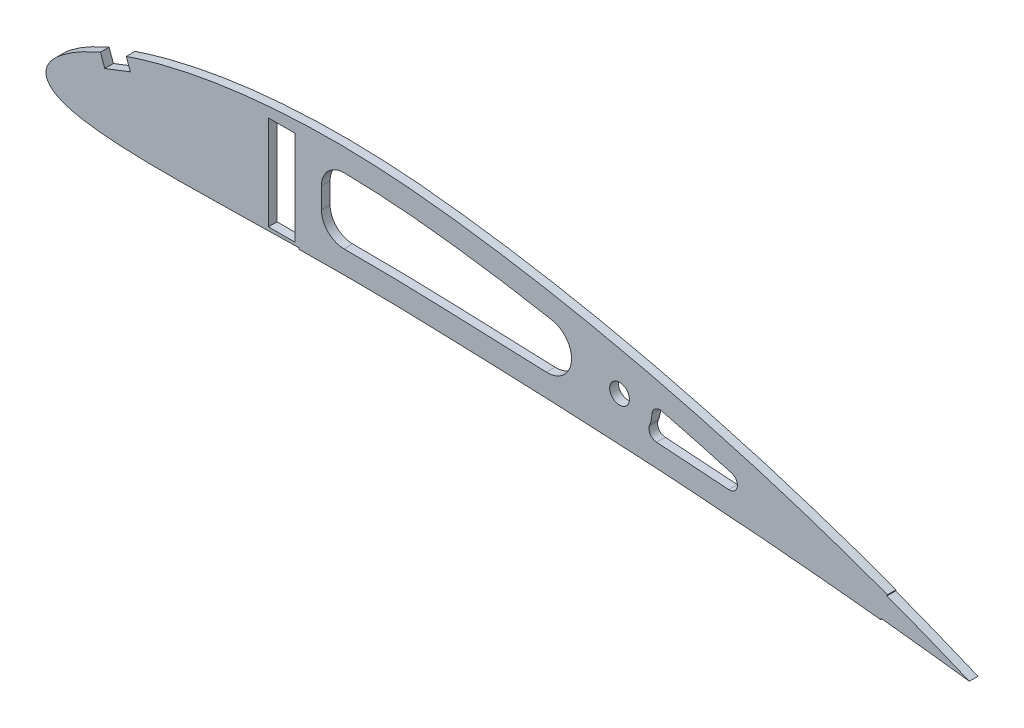
SolidWorks part; units mm, degrees
ref_plane "Front Plane" through (0, 0, 0) normal (0, 0, 1) x (1, 0, 0)
ref_plane "Top Plane" through (0, 0, 0) normal (0, 1, 0) x (1, 0, 0)
ref_plane "Right Plane" through (0, 0, 0) normal (1, 0, 0) x (0, 0, -1)
sketch "Sketch1" plane through (0, 0, 0) normal (0, 0, 1) x (1, 0, 0)
  line L0 (2547.2763, 3279.2563) -> (2536.8623, 3279.2563)
  line L1 (2547.2763, 3242.1233) -> (2536.8623, 3242.1233)
  line L2 (2536.8623, 3279.2563) -> (2536.8623, 3242.1233)
  line L3 (2547.2763, 3279.2563) -> (2547.2763, 3242.1233)
  line L4 (2548.8638, 3240.993) -> (2548.8703, 3240.4726)
  line L5 (2472.4468, 3263.9008) -> (2470.7661, 3268.615)
  line L6 (2482.5221, 3267.7862) -> (2480.9228, 3272.272)
  line L7 (2780.3662, 3238.0365) -> (2780.5427, 3238.5099)
  line L8 (2778.0193, 3229.2488) -> (2777.9678, 3228.7249)
  line L9 (2557.7538, 3266.5426) -> (2557.7538, 3258.3782)
  line L10 (2472.4468, 3263.9008) -> (2482.5221, 3267.7862)
  circle A0 centre (2675.1058, 3254.3467) radius 3.8862
  arc A1 (2686.9168, 3249.475) -> (2687.8696, 3253.7841) centre (2675.1058, 3254.3467) ccw
  arc A2 (2566.7617, 3275.4318) -> (2557.7538, 3266.5426) centre (2566.6438, 3266.5426) ccw
  arc A3 (2557.7538, 3258.3782) -> (2566.6631, 3249.4882) centre (2566.6438, 3258.3782) ccw
  arc A4 (2646.2636, 3247.3079) -> (2648.4261, 3266.1879) centre (2646.6833, 3256.8237) ccw
  arc A5 (2691.8173, 3256.723) -> (2687.8696, 3253.7841) centre (2691.0416, 3253.6442) ccw
  arc A6 (2686.9168, 3249.475) -> (2689.6687, 3245.0947) centre (2689.8519, 3248.2644) ccw
  arc A7 (2718.0983, 3243.1533) -> (2719.2039, 3249.3723) centre (2718.3306, 3246.3198) ccw
  spline S0 degree 3 poles (2470.7661, 3268.615) (2470.6464, 3268.5629) (2470.5267, 3268.5106) (2466.9137, 3266.9245) (2463.4641, 3265.2491) (2457.8844, 3261.8204) (2455.6089, 3260.227) (2451.9641, 3256.8801) (2450.4657, 3255.1523) (2449.2892, 3251.9455) (2449.1568, 3250.6446) (2449.952, 3248.2689) (2450.8099, 3247.2197) (2452.68, 3245.7373) (2453.701, 3245.1797) (2455.7378, 3244.2406) (2456.8244, 3243.8699) (2460.2041, 3242.8122) (2462.5683, 3242.3522) (2467.3207, 3241.5767) (2469.7198, 3241.3109) (2476.9483, 3240.6694) (2481.785, 3240.4161) (2491.4695, 3240.186) (2496.312, 3240.1748) (2511.0794, 3240.2587) (2520.9791, 3240.4891) (2536.8784, 3240.7726) (2542.8705, 3240.9074) (2548.8638, 3240.993) knots 14.135709 14.135709 14.135709 14.135709 14.151211 14.151211 14.604184 14.604184 14.932416 14.932416 15.199765 15.199765 15.362932 15.362932 15.5261 15.5261 15.66286 15.66286 15.79962 15.79962 16.086125 16.086125 16.37263 16.37263 16.945639 16.945639 17.518648 17.518648 18.689255 18.689255 19.396987 19.396987 19.396987 19.396987
  spline S1 degree 3 poles (2548.8703, 3240.4726) (2549.8808, 3240.4853) (2552.5653, 3240.5206) (2556.9478, 3240.5815) (2562.0305, 3240.5832) (2567.1738, 3240.5984) (2572.378, 3240.6141) (2577.6546, 3240.5818) (2582.9782, 3240.4869) (2588.3501, 3240.441) (2593.7796, 3240.2561) (2599.3074, 3240.102) (2604.9087, 3239.9235) (2610.5722, 3239.7714) (2616.2572, 3239.5268) (2621.9699, 3239.3814) (2627.6798, 3239.1505) (2633.4021, 3238.9385) (2639.1368, 3238.7344) (2644.8687, 3238.47) (2650.5883, 3238.2177) (2656.2963, 3237.9855) (2661.9877, 3237.6642) (2667.6718, 3237.4605) (2673.3112, 3237.1079) (2678.9152, 3236.7998) (2684.4815, 3236.4804) (2690.0115, 3236.178) (2695.4894, 3235.8325) (2700.9022, 3235.444) (2706.2541, 3235.073) (2711.544, 3234.7) (2716.7484, 3234.3451) (2721.8762, 3233.9542) (2726.912, 3233.5005) (2731.8817, 3233.1464) (2736.7578, 3232.7096) (2741.5391, 3232.3205) (2746.2156, 3231.8664) (2750.7708, 3231.441) (2755.2146, 3231.0186) (2759.5346, 3230.6) (2763.7464, 3230.2132) (2767.8261, 3229.7476) (2771.7933, 3229.3935) (2775.1515, 3228.9974) (2777.2, 3228.8005) (2777.9678, 3228.7249) knots 19.396956 19.396956 19.396956 19.396956 19.516306 19.714059 19.914611 20.11662 20.32154 20.529276 20.739841 20.950405 21.163745 21.381461 21.603554 21.825647 22.050605 22.275616 22.500574 22.725533 22.95195 23.178326 23.403242 23.628157 23.85304 24.076496 24.299895 24.520375 24.739394 24.958414 25.174499 25.387659 25.599359 25.808139 26.013999 26.215484 26.415525 26.611171 26.803913 26.993735 27.177747 27.35884 27.534095 27.704971 27.871469 28.033634 28.189916 28.341868 28.432981 28.432981 28.432981 28.432981
  spline S2 degree 3 poles (2780.5427, 3238.5099) (2778.253, 3239.3638) (2775.9733, 3240.2331) (2770.711, 3242.1161) (2767.7251, 3243.1682) (2758.7488, 3246.3574) (2752.6839, 3248.3448) (2740.5388, 3252.2622) (2734.4556, 3254.1832) (2722.2133, 3257.7846) (2716.0661, 3259.5027) (2703.7593, 3262.9004) (2697.5661, 3264.44) (2685.1978, 3267.5616) (2678.9801, 3268.9456) (2659.2455, 3273.2858) (2645.7434, 3275.8596) (2623.3857, 3279.4092) (2614.7201, 3280.6329) (2599.842, 3282.3445) (2593.7119, 3283.0102) (2581.3916, 3283.863) (2575.2189, 3284.1559) (2562.8836, 3284.4118) (2556.7118, 3284.3475) (2544.3747, 3283.8423) (2538.2135, 3283.4424) (2520.0352, 3281.6377) (2508.0643, 3279.6666) (2491.1379, 3275.4904) (2485.9704, 3274.0078) (2480.9228, 3272.272) knots 1.615896 1.615896 1.615896 1.615896 1.904436 1.904436 2.277217 2.277217 3.031526 3.031526 3.785836 3.785836 4.540146 4.540146 5.294456 5.294456 6.048766 6.048766 7.680004 7.680004 8.718619 8.718619 9.449269 9.449269 10.17992 10.17992 10.910571 10.910571 11.641222 11.641222 13.074039 13.074039 13.708237 13.708237 13.708237 13.708237
  spline S3 degree 3 poles (2812.8112, 3225.1535) (2811.7427, 3225.6004) (2810.661, 3226.0459) (2805.162, 3228.3268) (2800.7468, 3230.1145) (2791.811, 3233.7358) (2787.3909, 3235.4313) (2782.0553, 3237.4098) (2781.2108, 3237.7233) (2780.3662, 3238.0365) knots 0.240373 0.240373 0.240373 0.240373 0.376825 0.376825 0.943228 0.943228 1.509632 1.509632 1.616177 1.616177 1.616177 1.616177
  spline S4 degree 3 poles (2778.0193, 3229.2488) (2779.1748, 3229.1218) (2780.3303, 3228.9923) (2787.9969, 3228.1147) (2794.5403, 3227.4058) (2804.9356, 3226.1265) (2808.8293, 3225.6065) (2812.8112, 3225.1535) knots 28.432747 28.432747 28.432747 28.432747 28.56999 28.56999 29.343341 29.343341 29.813814 29.813814 29.813814 29.813814
  spline S5 degree 3 poles (2689.6687, 3245.0947) (2690.9236, 3245.0221) (2692.183, 3244.947) (2699.0659, 3244.5114) (2704.6007, 3244.0991) (2712.7745, 3243.5271) (2715.4243, 3243.3495) (2718.0983, 3243.1533) knots 24.92366 24.92366 24.92366 24.92366 25.070609 25.070609 25.727122 25.727122 26.039952 26.039952 26.039952 26.039952
  spline S6 degree 3 poles (2566.6631, 3249.4882) (2567.4398, 3249.4899) (2568.2183, 3249.4917) (2573.5871, 3249.5046) (2578.3279, 3249.4494) (2585.825, 3249.3471) (2589.0364, 3249.3044) (2595.1651, 3249.1134) (2598.1673, 3249.028) (2604.2577, 3248.8413) (2607.2482, 3248.763) (2612.8674, 3248.5744) (2615.291, 3248.4666) (2620.1241, 3248.3152) (2622.6619, 3248.2435) (2627.6217, 3248.0544) (2630.0511, 3247.9585) (2637.0527, 3247.7017) (2641.7061, 3247.5089) (2646.2636, 3247.3079) knots 20.098452 20.098452 20.098452 20.098452 20.190363 20.190363 20.729095 20.729095 21.088164 21.088164 21.447233 21.447233 21.806302 21.806302 22.096768 22.096768 22.387234 22.387234 22.677701 22.677701 23.217184 23.217184 23.217184 23.217184
  spline S7 degree 3 poles (2719.2039, 3249.3723) (2714.2381, 3250.7929) (2709.2315, 3252.1959) (2700.185, 3254.6129) (2696.0201, 3255.6641) (2691.8173, 3256.723) knots 4.06038 4.06038 4.06038 4.06038 4.675696 4.675696 5.188469 5.188469 5.188469 5.188469
  spline S8 degree 3 poles (2648.4261, 3266.1879) (2641.5924, 3267.4597) (2634.7338, 3268.6279) (2619.3252, 3271.0131) (2610.8711, 3272.1462) (2595.7157, 3273.8504) (2589.3146, 3274.4493) (2577.4277, 3275.1499) (2572.0848, 3275.3612) (2566.7617, 3275.4318) knots 6.961493 6.961493 6.961493 6.961493 7.794516 7.794516 8.825426 8.825426 9.617156 9.617156 10.265753 10.265753 10.265753 10.265753
extrude "Boss-Extrude1" add sketch "Sketch1" along normal blind 3.4036
